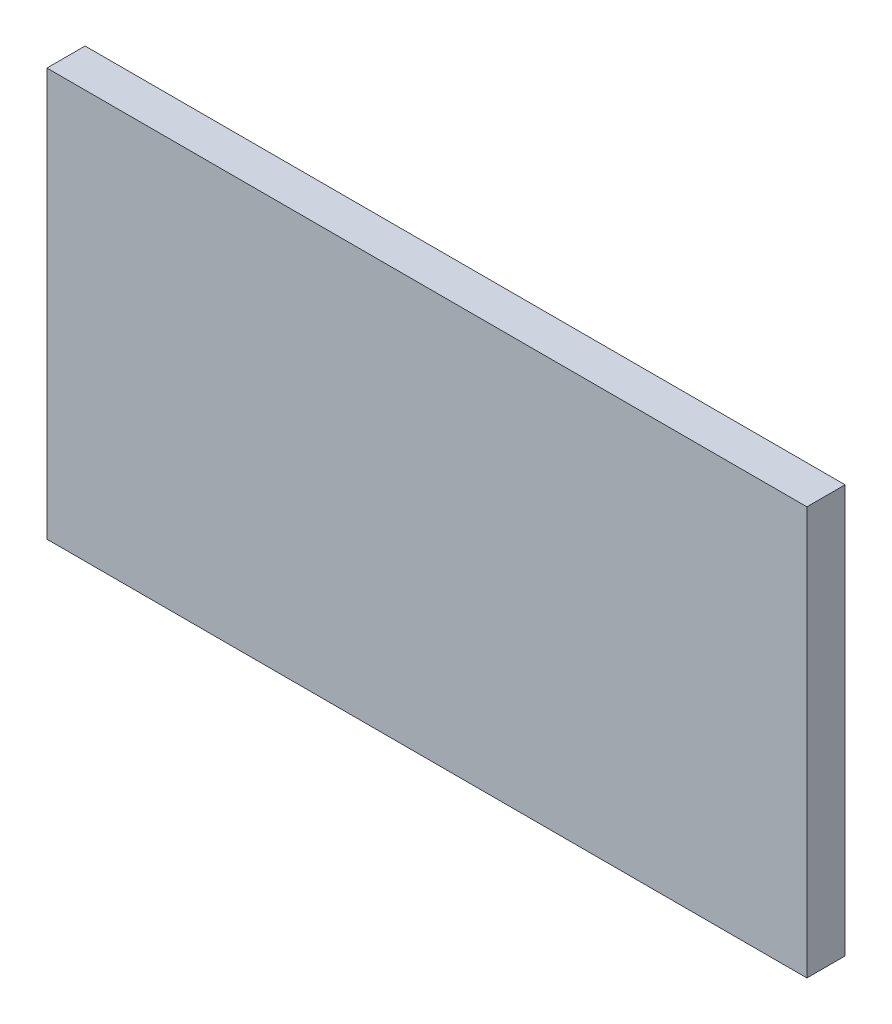
SolidWorks part; units mm, degrees
ref_plane "Front Plane" through (0, 0, 0) normal (0, 0, 1) x (1, 0, 0)
ref_plane "Top Plane" through (0, 0, 0) normal (0, 1, 0) x (1, 0, 0)
ref_plane "Right Plane" through (0, 0, 0) normal (1, 0, 0) x (0, 0, -1)
sketch "Sketch1" plane through (0, 0, 0) normal (0, 0, 1) x (1, 0, 0)
  line L1 (-26.8651, 13.8335) -> (32.8797, 13.8335)
  line L2 (-26.8651, 13.8335) -> (-26.8651, -18.2442)
  line L3 (-26.8651, -18.2442) -> (32.8797, -18.2442)
  line L4 (32.8797, 13.8335) -> (32.8797, -18.2442)
extrude "Boss-Extrude1" add sketch "Sketch1" along normal blind 3
